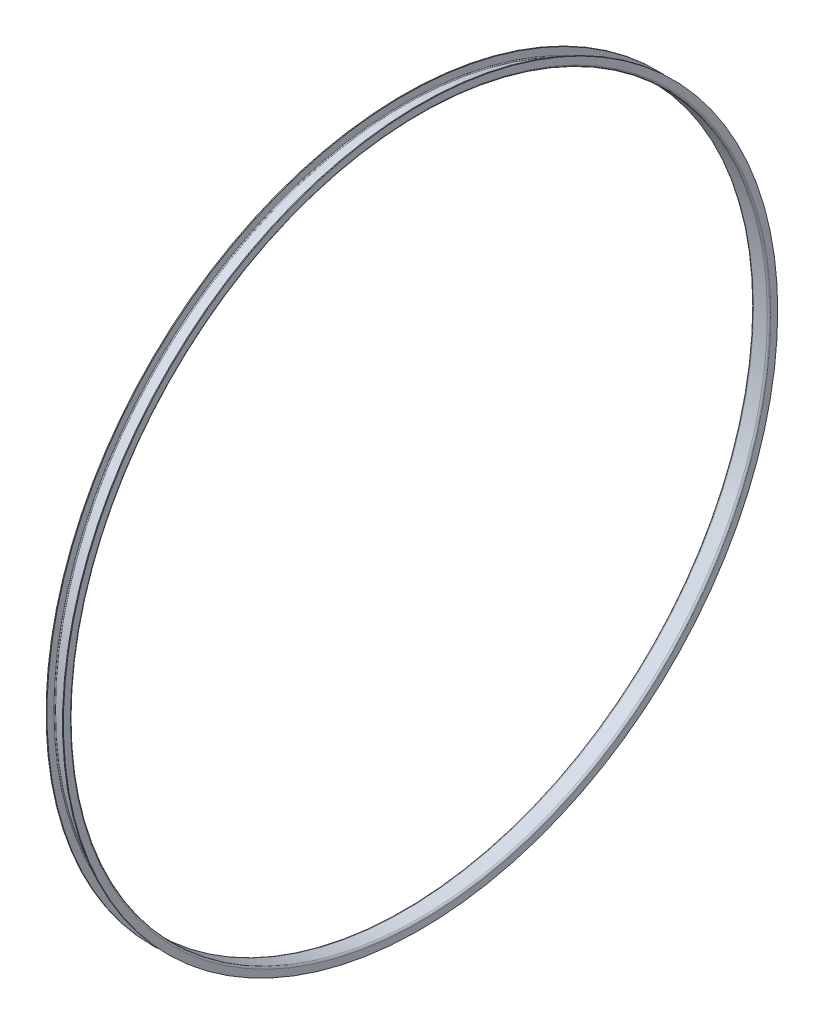
SolidWorks part; units mm, degrees
material "ASTM A36 Steel"
ref_plane "Front Plane" through (0, 0, 0) normal (0, 0, 1) x (1, 0, 0)
ref_plane "Top Plane" through (0, 0, 0) normal (0, 1, 0) x (1, 0, 0)
ref_plane "Right Plane" through (0, 0, 0) normal (1, 0, 0) x (0, 0, -1)
sketch "Sketch1" plane through (0, 0, 0) normal (0, 0, 1) x (1, 0, 0)
  line L0 (-38, 75.5372) -> (-38, 59.5372)
  line L1 (-34, 55.5372) -> (-2, 55.5372)
  line L2 (2, 59.5372) -> (2, 75.5372)
  line L3 (2, 75.5372) -> (0, 75.5372)
  line L4 (0, 75.5372) -> (0, 59.5372)
  line L5 (-2, 57.5372) -> (-34, 57.5372)
  line L6 (-36, 59.5372) -> (-36, 75.5372)
  line L7 (-36, 75.5372) -> (-38, 75.5372)
  line L8 (63.9445, -749.4628) -> (-124.1409, -749.4628) construction
  arc A0 (-2, 55.5372) -> (2, 59.5372) centre (-2, 59.5372) ccw
  arc A1 (-34, 55.5372) -> (-38, 59.5372) centre (-34, 59.5372) cw
  arc A2 (-2, 57.5372) -> (0, 59.5372) centre (-2, 59.5372) ccw
  arc A3 (-34, 57.5372) -> (-36, 59.5372) centre (-34, 59.5372) cw
  point P11 (2, 55.5372)
  point P14 (-38, 55.5372)
  dimension "D7" = 4
  dimension "D8" = 2
  dimension "D1" = 40
  dimension "D2" = 20
  dimension "D3" = 20
  dimension "D4" = 2
  dimension "D5" = 2
  dimension "D6" = 2
  dimension "D9" = 825
revolve "Revolve1" add sketch "Sketch1" angle 360 about L8
sketch "Sketch2" plane through (2, 0, 0) normal (1, 0, 0) x (0, 0, -1)
  line L0 (0, -749.4628) -> (1025.3442, -749.4628)
  line L1 (1025.3442, -749.4628) -> (0, -749.4628)
  line L2 (0, -749.4628) -> (0, 383.8124)
